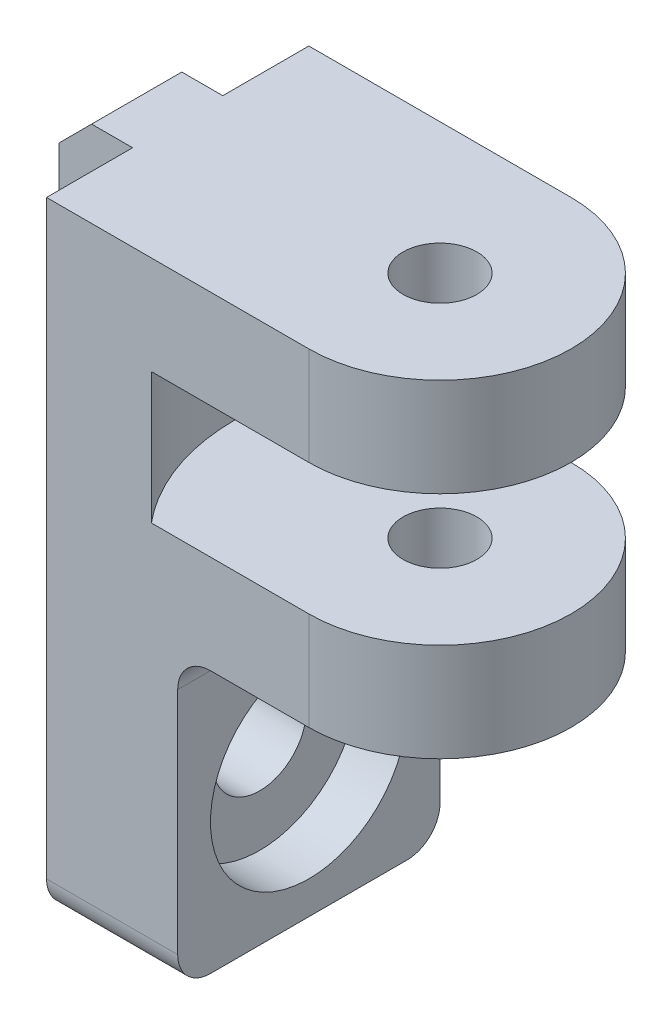
SolidWorks part; units mm, degrees
ref_plane "Front Plane" through (0, 0, 0) normal (0, 0, 1) x (1, 0, 0)
ref_plane "Top Plane" through (0, 0, 0) normal (0, 1, 0) x (1, 0, 0)
ref_plane "Right Plane" through (0, 0, 0) normal (1, 0, 0) x (0, 0, -1)
sketch "Sketch1" plane through (0, 0, 0) normal (1, 0, 0) x (0, 0, -1)
  line L0 (-32.8466, 35.9115) -> (-32.8466, -2.0885)
  line L1 (-48.8466, 35.9115) -> (-32.8466, 35.9115)
  line L5 (-32.8466, -2.0885) -> (-48.8466, -2.0885)
  line L6 (-48.8466, -2.0885) -> (-48.8466, 35.9115)
  dimension "D9" = 16
  dimension "D10" = 38
extrude "Boss-Extrude1" add sketch "Sketch1" along normal blind 8
sketch "Sketch2" plane through (0, 0, 0) normal (-1, 0, 0) x (0, 0, 1)
  line L0 (40.8466, 5.9115) -> (40.8466, 24.9115) construction
  line L1 (48.8466, 35.9115) -> (48.8466, -2.0885) construction
  line L2 (32.8466, 35.9115) -> (48.8466, 35.9115) construction
  line L3 (38.0966, 35.9115) -> (43.5966, 35.9115)
  line L4 (38.0966, 35.9115) -> (38.0966, 13.9115)
  line L5 (38.0966, 13.9115) -> (43.5966, 13.9115)
  line L6 (43.5966, 35.9115) -> (43.5966, 13.9115)
  line L7 (38.0966, 35.9115) -> (43.5966, 13.9115) construction
  line L8 (38.0966, 13.9115) -> (43.5966, 35.9115) construction
  point P5 (40.8466, 24.9115)
  dimension "D1" = 5.5
  dimension "D3" = 8
extrude "Boss-Extrude2" add sketch "Sketch2" along normal blind 4.5
sketch "Sketch6" plane through (0, 35.9115, 0) normal (0, -1, 0) x (1, 0, 0)
  line L0 (8, 48.8466) -> (16, 48.8466)
  line L2 (16, 32.8466) -> (8, 32.8466)
  line L3 (8, 32.8466) -> (8, 48.8466)
  arc A0 (16, 32.8466) -> (16, 48.8466) centre (16, 40.8466) ccw
  circle A1 centre (16, 40.8466) radius 2.25
  dimension "D2" = 4.5
  dimension "D1" = 8
extrude "Boss-Extrude3" add sketch "Sketch6" along normal blind 20 contours A0 L0 L3 L2
fillet "Fillet6" radius 2 1 edges at (8, 15.9115, 40.8466)
chamfer "Chamfer1" distance 2 angle 45 2 edges at (-4.5, 13.9115, 40.8466) (-4.5, 35.9115, 40.8466)
sketch "Sketch7" plane through (8, 0, 0) normal (1, 0, 0) x (0, 0, -1)
  line L0 (-48.8466, -2.0885) -> (-32.8466, -2.0885) construction
  line L1 (-32.8466, -2.0885) -> (-32.8466, 13.9115) construction
  circle A0 centre (-40.8466, 5.9115) radius 2.85
  dimension "D1" = 8
  dimension "D2" = 8
extrude "Cut-Extrude1" cut sketch "Sketch7" against normal blind 10
sketch "Sketch8" plane through (8, 0, 0) normal (1, 0, 0) x (0, 0, -1)
  circle A0 centre (-40.8466, 5.9115) radius 6
extrude "Cut-Extrude2" cut sketch "Sketch8" against normal blind 3
sketch "Sketch9" plane through (0, 35.9115, 0) normal (0, 1, 0) x (1, 0, 0)
  circle A0 centre (16, -40.8466) radius 12.5
  arc A1 (16, -48.8466) -> (16, -32.8466) centre (16, -40.8466) ccw construction
  dimension "D1" = 4.5
extrude "Cut-Extrude3" cut sketch "Sketch9" against normal mid plane 8 from offset 10 offset against normal yes
fillet "Fillet7" radius 2 2 edges at (4, -2.0885, 32.8466) (4, -2.0885, 48.8466)
